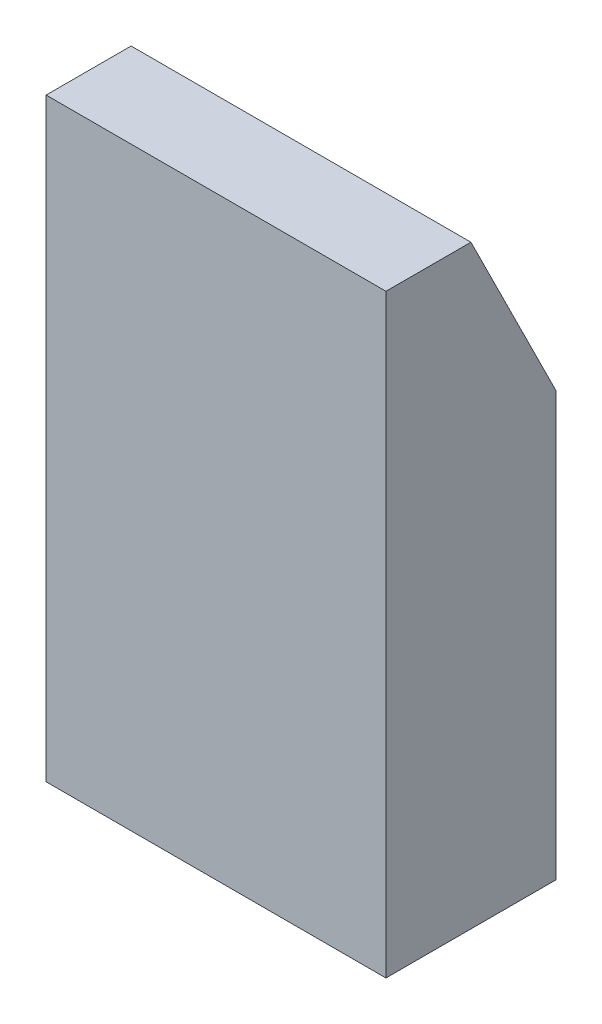
SolidWorks part; units mm, degrees
ref_plane "Front Plane" through (0, 0, 0) normal (0, 0, 1) x (1, 0, 0)
ref_plane "Top Plane" through (0, 0, 0) normal (0, 1, 0) x (1, 0, 0)
ref_plane "Right Plane" through (0, 0, 0) normal (1, 0, 0) x (0, 0, -1)
sketch "Sketch1" plane through (0, 0, 0) normal (0, 1, 0) x (1, 0, 0)
  line L0 (0, 0) -> (40, 0)
  line L1 (40, 0) -> (40, 20)
  line L2 (40, 20) -> (0, 20)
  line L3 (0, 20) -> (0, 0)
  dimension "D1" = 40
  dimension "D2" = 20
extrude "Boss-Extrude1" add sketch "Sketch1" along normal blind 70
sketch "Sketch2" plane through (0, 0, 0) normal (1, 0, 0) x (0, 0, -1)
  line L0 (10, 70) -> (20, 49.892)
  line L1 (0, 70) -> (20, 70) construction
  line L2 (20, 70) -> (20, 0) construction
  line L3 (20, 49.892) -> (27.7406, 66.2821)
  line L4 (27.7406, 66.2821) -> (20, 74.9731)
  line L5 (20, 74.9731) -> (10, 70)
extrude "Cut-Extrude1" cut sketch "Sketch2" along normal blind 40
